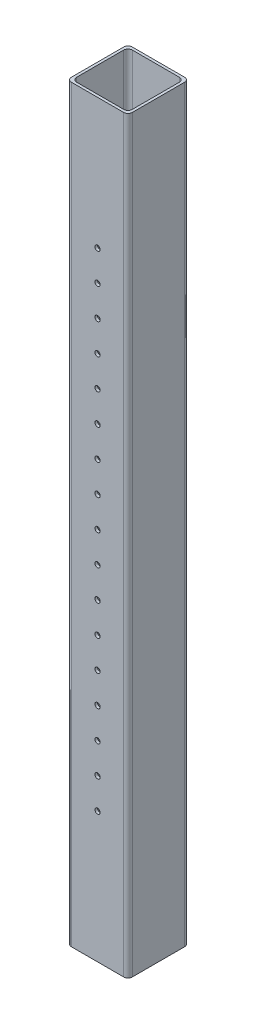
SolidWorks part; units mm, degrees
ref_plane "Front Plane" through (0, 0, 0) normal (0, 0, 1) x (1, 0, 0)
ref_plane "Top Plane" through (0, 0, 0) normal (0, 1, 0) x (1, 0, 0)
ref_plane "Right Plane" through (0, 0, 0) normal (1, 0, 0) x (0, 0, -1)
sketch "Sketch1" plane through (0, 0, 0) normal (0, 1, 0) x (1, 0, 0)
  line L0 (3, 67) -> (67, 67)
  line L1 (0, 0) -> (70, 0)
  line L2 (0, 0) -> (0, 70)
  line L3 (0, 70) -> (70, 70)
  line L4 (70, 0) -> (70, 70)
  line L5 (67, 3) -> (67, 67)
  line L6 (3, 3) -> (67, 3)
  line L7 (3, 3) -> (3, 67)
  dimension "D1" = 70
  dimension "D2" = 70
  dimension "D3" = 3
extrude "Boss-Extrude1" add sketch "Sketch1" along normal blind 860 contours L7 L6 L5 L0 | L1 L4 L3 L2 L6 L7 L0 L5
fillet "Fillet1" radius 5 8 edges at (70, 430, 0) (67, 430, -3) (70, 430, -70) (67, 430, -67) (3, 430, -67) (0, 430, -70) (0, 430, 0) (3, 430, -3)
sketch "Sketch2" plane through (0, 0, -70) normal (0, 0, -1) x (-1, 0, 0)
  line L0 (-65, 430) -> (-5, 430) construction
  line L3 (-65, 860) -> (-65, 0) construction
  line L6 (-5, 0) -> (-5, 860) construction
  circle A19 centre (-35, 430) radius 3
extrude "Cut-Extrude1" cut sketch "Sketch2" against normal blind 70
pattern_linear "LPattern1" count 9 spacing 35 along (0, -1, 0) count 9 spacing 35 along (0, 1, 0) of "Cut-Extrude1"
